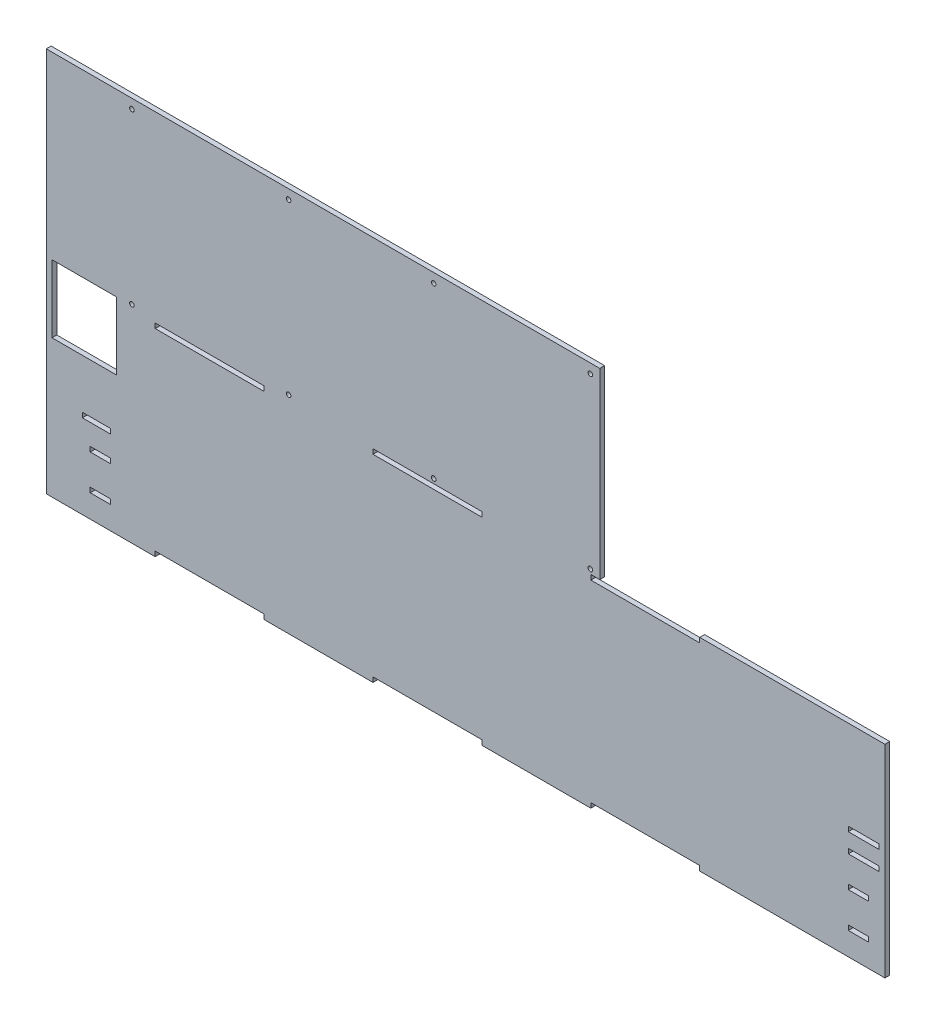
SolidWorks part; units mm, degrees
ref_plane "Front Plane" through (0, 0, 0) normal (0, 0, 1) x (1, 0, 0)
ref_plane "Top Plane" through (0, 0, 0) normal (0, 1, 0) x (1, 0, 0)
ref_plane "Right Plane" through (0, 0, 0) normal (1, 0, 0) x (0, 0, -1)
sketch "Sketch1" plane through (0, 0, 0) normal (0, 0, 1) x (1, 0, 0)
  line L1 (0, 0) -> (550, 0) construction
  line L2 (0, 0) -> (0, 132.75)
  line L4 (550, 0) -> (550, 132.75)
  line L5 (71.4286, 132.75) -> (71.4286, 129.575)
  line L6 (71.4286, 129.575) -> (142.8571, 129.575)
  line L7 (142.8571, 129.575) -> (142.8571, 132.75)
  line L9 (214.2857, 132.75) -> (214.2857, 129.575)
  line L10 (214.2857, 129.575) -> (285.7143, 129.575)
  line L11 (285.7143, 129.575) -> (285.7143, 132.75)
  line L13 (357.1429, 132.75) -> (357.1429, 129.575)
  line L14 (357.1429, 129.575) -> (428.5714, 129.575)
  line L15 (428.5714, 129.575) -> (428.5714, 132.75)
  line L17 (0, 66.375) -> (550, 66.375) construction
  line L18 (428.5714, 0) -> (550, 0)
  line L19 (428.5714, 3.175) -> (428.5714, 0)
  line L20 (357.1429, 3.175) -> (428.5714, 3.175)
  line L21 (357.1429, 0) -> (357.1429, 3.175)
  line L22 (285.7143, 0) -> (357.1429, 0)
  line L23 (285.7143, 3.175) -> (285.7143, 0)
  line L24 (214.2857, 3.175) -> (285.7143, 3.175)
  line L25 (214.2857, 0) -> (214.2857, 3.175)
  line L26 (142.8571, 0) -> (214.2857, 0)
  line L27 (142.8571, 3.175) -> (142.8571, 0)
  line L28 (71.4286, 3.175) -> (142.8571, 3.175)
  line L29 (71.4286, 0) -> (71.4286, 3.175)
  line L30 (0, 0) -> (71.4286, 0)
  line L31 (546, 61.675) -> (546, 66.375) construction
  line L32 (546, 61.675) -> (526, 61.675)
  line L33 (546, 61.675) -> (546, 58.5)
  line L34 (546, 58.5) -> (526, 58.5)
  line L35 (526, 61.675) -> (526, 58.5)
  line L36 (526, 71.075) -> (546, 71.075)
  line L37 (526, 71.075) -> (526, 74.25)
  line L38 (526, 74.25) -> (546, 74.25)
  line L39 (546, 71.075) -> (546, 74.25)
  line L40 (23.683, 66.375) -> (23.683, 90.505) construction
  line L53 (285.7143, 132.75) -> (214.2857, 132.75)
  line L54 (142.8571, 132.75) -> (71.4286, 132.75)
  line L55 (328.2222, 252.75) -> (363, 252.75) construction
  line L56 (328.2222, 252.75) -> (363, 252.75)
  line L57 (363, 252.75) -> (363, 228.115) construction
  line L58 (363, 252.75) -> (363, 228.115)
  line L59 (363, 228.115) -> (363, 132.75)
  line L60 (363, 132.75) -> (357.1429, 132.75)
  line L61 (428.5714, 132.75) -> (550, 132.75)
  line L62 (328.2222, 252.75) -> (0, 252.75)
  line L63 (0, 252.75) -> (0, 132.75)
  line L64 (539.333, 15) -> (526, 15)
  line L65 (3.8, 134.855) -> (46.1, 134.855)
  line L66 (3.8, 134.855) -> (3.8, 90.505)
  line L67 (3.8, 90.505) -> (46.1, 90.505)
  line L68 (46.1, 134.855) -> (46.1, 90.505)
  line L69 (23.683, 58.175) -> (42.183, 58.175)
  line L70 (23.683, 58.175) -> (23.683, 55)
  line L71 (23.683, 55) -> (42.183, 55)
  line L72 (42.183, 58.175) -> (42.183, 55)
  line L73 (42.183, 15) -> (28.85, 15)
  line L74 (42.183, 15) -> (42.183, 18.175)
  line L75 (42.183, 18.175) -> (28.85, 18.175)
  line L76 (28.85, 15) -> (28.85, 18.175)
  line L77 (42.183, 38.175) -> (28.85, 38.175)
  line L78 (42.183, 38.175) -> (42.183, 41.35)
  line L79 (42.183, 41.35) -> (28.85, 41.35)
  line L80 (28.85, 38.175) -> (28.85, 41.35)
  line L81 (539.333, 15) -> (539.333, 18.175)
  line L82 (539.333, 18.175) -> (526, 18.175)
  line L83 (526, 15) -> (526, 18.175)
  line L84 (539.333, 38.175) -> (526, 38.175)
  line L85 (539.333, 38.175) -> (539.333, 41.35)
  line L86 (539.333, 41.35) -> (526, 41.35)
  line L87 (526, 38.175) -> (526, 41.35)
  circle A0 centre (56.175, 246.575) radius 1.5 construction
  circle A1 centre (158.9208, 135.75) radius 1.5 construction
  circle A2 centre (158.9208, 246.575) radius 1.5 construction
  circle A3 centre (254.0792, 246.575) radius 1.5 construction
  circle A4 centre (254.0792, 135.75) radius 1.5 construction
  circle A5 centre (356.825, 135.75) radius 1.5 construction
  circle A6 centre (356.825, 246.575) radius 1.5 construction
  circle A7 centre (56.175, 246.575) radius 1.5
  circle A8 centre (158.9208, 135.75) radius 1.5
  circle A9 centre (158.9208, 246.575) radius 1.5
  circle A10 centre (254.0792, 246.575) radius 1.5
  circle A11 centre (254.0792, 135.75) radius 1.5
  circle A12 centre (356.825, 135.75) radius 1.5
  circle A13 centre (356.825, 246.575) radius 1.5
  circle A15 centre (56.175, 135.75) radius 1.5 construction
  circle A16 centre (56.175, 135.75) radius 1.5
  point P87 (0, 0)
  point P96 (0, 0)
  point P97 (0, 0)
  point P98 (0, 0)
  dimension "D1" = 550
  dimension "D2" = 132.75
  dimension "D3" = 3.175
  dimension "D4" = 24.13
  dimension "D5" = 3.8
  dimension "D6" = 44.35
  dimension "D7" = 42.3
  dimension "D8" = 4
  dimension "D9" = 20
  dimension "D10" = 3.175
  dimension "D11" = 4.7
  dimension "D12" = 4.7
  dimension "D13" = 3.175
  dimension "D14" = 18.5
  dimension "D15" = 55
  dimension "D16" = 3.175
  dimension "D17" = 3.175
  dimension "D18" = 13.333
  dimension "D19" = 13.333
  dimension "D20" = 20
  dimension "D21" = 15
  dimension "D22" = 3.175
  dimension "D23" = 3.175
  dimension "D24" = 13.333
  dimension "D25" = 13.333
  dimension "D26" = 20
  dimension "D27" = 15
extrude "Boss-Extrude1" add sketch "Sketch1" along normal blind 3.175
